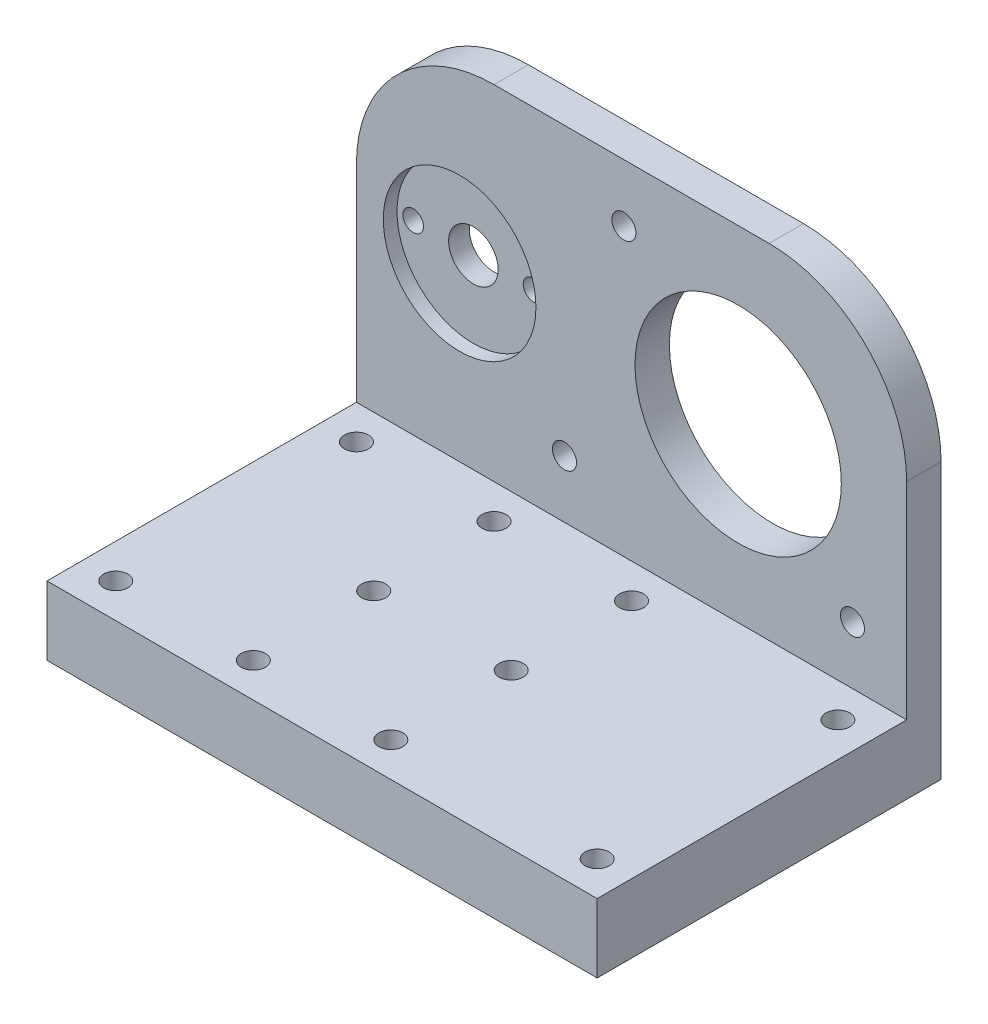
SolidWorks part; units mm, degrees
ref_plane "Front Plane" through (0, 0, 0) normal (0, 0, 1) x (1, 0, 0)
ref_plane "Top Plane" through (0, 0, 0) normal (0, 1, 0) x (1, 0, 0)
ref_plane "Right Plane" through (0, 0, 0) normal (1, 0, 0) x (0, 0, -1)
sketch "Sketch1" plane through (0, 0, 0) normal (0, 0, 1) x (1, 0, 0)
  line L1 (-120, 24) -> (-40, 24)
  line L2 (-120, 24) -> (-120, -26)
  line L3 (-120, -26) -> (-40, -26)
  line L4 (-40, 24) -> (-40, -26)
  dimension "D1" = 50
  dimension "D2" = 80
extrude "Boss-Extrude1" add sketch "Sketch1" along normal blind 5
sketch "Sketch2" plane through (0, 0, 5) normal (0, 0, 1) x (1, 0, 0)
  line L0 (-120, -26) -> (-40, -26) construction
  line L2 (-120, 24) -> (-120, -26) construction
  circle A0 centre (-105, -1) radius 3.6
  dimension "D1" = 7.2
  dimension "D2" = 25
  dimension "D3" = 15
extrude "Cut-Extrude1" cut sketch "Sketch2" against normal through all
sketch "Sketch3" plane through (0, 0, 5) normal (0, 0, 1) x (1, 0, 0)
  line L0 (-105, 2.6) -> (-105, -1) construction
  line L1 (-105, -1) -> (-101.4, -1) construction
  circle A0 centre (-96.25, -1) radius 1.5
  circle A1 centre (-105, -1) radius 3.6 construction
  circle A2 centre (-113.75, -1) radius 1.5
  dimension "D2" = 3
  dimension "D3" = 17.5
extrude "Cut-Extrude2" cut sketch "Sketch3" against normal through all contours A2 | A0
sketch "Sketch4" plane through (0, 0, 5) normal (0, 0, 1) x (1, 0, 0)
  circle A0 centre (-105, -1) radius 11.1
  circle A1 centre (-105, -1) radius 3.6 construction
  dimension "D1" = 22.2
extrude "Cut-Extrude3" cut sketch "Sketch4" against normal blind 2
sketch "Sketch5" plane through (0, 0, 5) normal (0, 0, 1) x (1, 0, 0)
  line L0 (-113.75, -1) -> (-27.4836, -1) construction
  circle A0 centre (-64.5, -1) radius 15
  circle A1 centre (-105, -1) radius 3.6 construction
  point P2 (0, 0)
  dimension "D1" = 30
  dimension "D2" = 40.5
extrude "Cut-Extrude4" cut sketch "Sketch5" against normal through all
sketch "Sketch6" plane through (0, 0, 5) normal (0, 0, 1) x (1, 0, 0)
  line L0 (-79.5, -1) -> (-49.5, -1) construction
  line L1 (-64.5, -1) -> (-53.8934, 9.6066) construction
  line L2 (-64.5, -1) -> (-75.1066, 9.6066) construction
  circle A0 centre (-81.117, 15.617) radius 1.75
  circle A2 centre (-64.5, -1) radius 15 construction
  circle A3 centre (-47.883, -17.617) radius 1.75
  dimension "D3" = 3.5
  dimension "D4" = 23.5
  dimension "D1" = 45
  dimension "D2" = 135
extrude "Cut-Extrude5" cut sketch "Sketch6" against normal through all
sketch "Sketch7" plane through (0, -26, 0) normal (0, -1, 0) x (1, 0, 0)
  line L0 (-120, 0) -> (-40, 0) construction
  line L1 (-120, 50) -> (-40, 50)
  line L2 (-120, 50) -> (-120, 0)
  line L3 (-120, 0) -> (-40, 0)
  line L4 (-40, 50) -> (-40, 0)
  dimension "D1" = 50
  dimension "D2" = 80
  dimension "D3" = 0
extrude "Boss-Extrude2" add sketch "Sketch7" along normal blind 10
fillet "Fillet1" radius 20 2 edges at (-120, 24, 2.5) (-40, 24, 2.5)
sketch "Sketch9" plane through (0, -26, 0) normal (0, 1, 0) x (1, 0, 0)
  line L0 (-120, -50) -> (-120, -5) construction
  line L3 (-120, -5) -> (-100, -5) construction
  circle A0 centre (-115, -10) radius 1.75
  circle A1 centre (-45, -10) radius 1.75
  circle A2 centre (-45, -45) radius 1.75
  circle A3 centre (-115, -45) radius 1.75
  circle A4 centre (-95, -10) radius 1.75
  circle A5 centre (-95, -45) radius 1.75
  circle A6 centre (-75, -10) radius 1.75
  circle A7 centre (-75, -45) radius 1.75
  dimension "D1" = 3.5
  dimension "D2" = 5
  dimension "D4" = 2
  dimension "D3" = 5
  dimension "D5" = 2
  dimension "D6" = 3
extrude "Cut-Extrude6" cut sketch "Sketch9" against normal through all and the other way through all
sketch "Sketch10" plane through (0, -26, 0) normal (0, 1, 0) x (1, 0, 0)
  line L0 (-75, -10) -> (-75, -45) construction
  line L1 (-95, -10) -> (-95, -45) construction
  circle A1 centre (-95, -27.5) radius 1.75
  circle A2 centre (-75, -27.5) radius 1.75
  circle A3 centre (-95, -10) radius 1.75 construction
  point P8 (0, 0)
  point P9 (0, 0)
extrude "Cut-Extrude7" cut sketch "Sketch10" against normal through all
sketch "Sketch11" plane through (0, 0, 5) normal (0, 0, 1) x (1, 0, 0)
  line L0 (-47.883, -17.617) -> (-111.3871, -17.617) construction
  line L1 (-64.5, -1) -> (-105, -1) construction
  line L2 (-84.75, 15.3485) -> (-84.75, -8.7617) construction
  circle A0 centre (-89.75, -17.617) radius 1.75
  point P11 (-84.75, -1)
  point P12 (0, 0)
  dimension "D1" = 3.5
  dimension "D2" = 5
extrude "Cut-Extrude8" cut sketch "Sketch11" against normal through all
